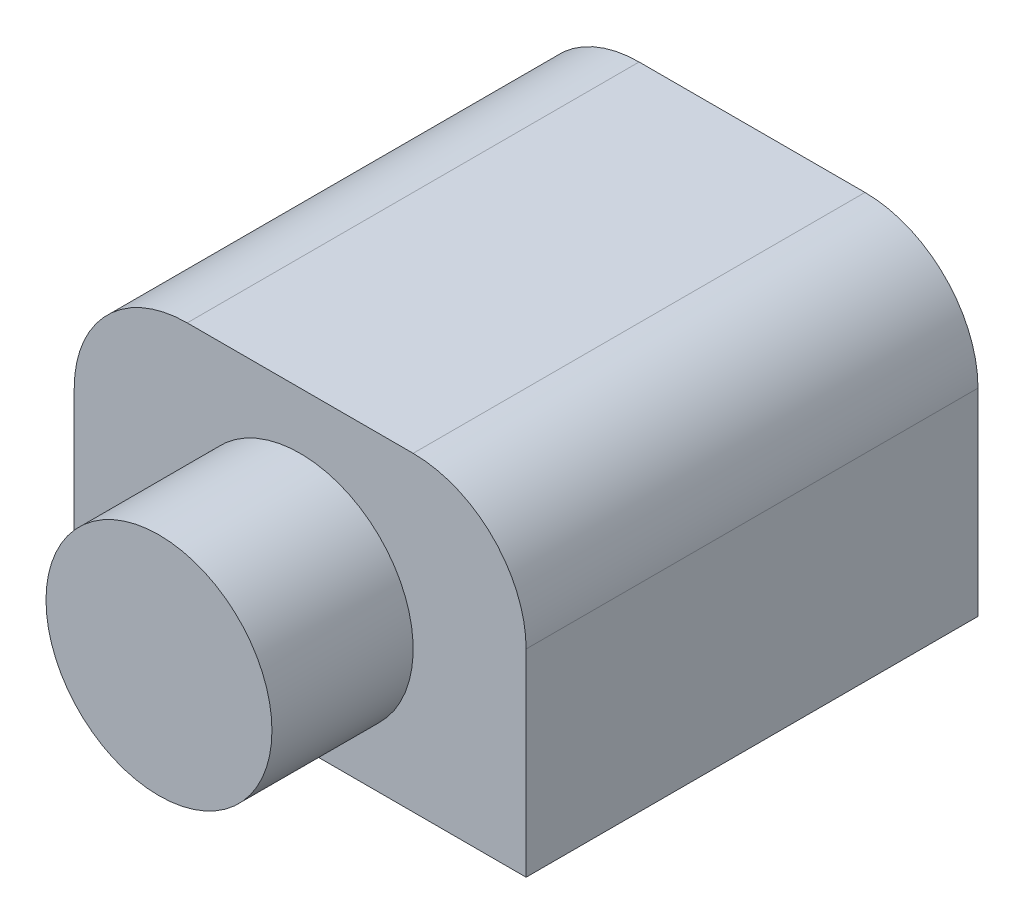
SolidWorks part; units mm, degrees
ref_plane "Plano frontal" through (0, 0, 0) normal (0, 0, 1) x (1, 0, 0)
ref_plane "Plano superior" through (0, 0, 0) normal (0, 1, 0) x (1, 0, 0)
ref_plane "Plano direito" through (0, 0, 0) normal (1, 0, 0) x (0, 0, -1)
sketch "Esboço1" plane through (0, 0, 0) normal (0, 1, 0) x (1, 0, 0)
  line L1 (40, -40) -> (-40, -40)
  line L2 (40, -40) -> (40, 40)
  line L3 (40, 40) -> (-40, 40)
  line L4 (-40, -40) -> (-40, 40)
  line L5 (40, -40) -> (-40, 40) construction
  line L6 (40, 40) -> (-40, -40) construction
  point P0 (0, 0)
  dimension "D1" = 80
extrude "Ressalto-extrusão1" add sketch "Esboço1" along normal blind 190
fillet "Filete2" radius 20 2 edges at (40, 190, 0) (-40, 190, 0)
sketch "Esboço2" plane through (0, 0, 40) normal (0, 0, 1) x (1, 0, 0)
  line L1 (-20, 190) -> (20, 190) construction
  line L2 (0, -52.3276) -> (0, 52.3276) construction
  circle A0 centre (0, 160) radius 20
  point P9 (0, 0)
  dimension "D1" = 40
  dimension "D2" = 30
extrude "Ressalto-extrusão2" add sketch "Esboço2" along normal blind 25
sketch "Esboço3" plane through (0, 0, 0) normal (0, -1, 0) x (-1, 0, 0)
  line L0 (40, -40) -> (-40, -40) construction
  line L1 (-35, 35) -> (35, 35)
  line L2 (-35, 35) -> (-35, -35)
  line L3 (-35, -35) -> (35, -35)
  line L4 (35, 35) -> (35, -35)
  line L5 (-35, 35) -> (35, -35) construction
  line L6 (-35, -35) -> (35, 35) construction
  point P0 (0, 0)
  dimension "D1" = 5
extrude "Corte-extrusão1" cut sketch "Esboço3" against normal blind 135
sketch "Esboço4" plane through (0, 0, 40) normal (0, 0, 1) x (1, 0, 0)
  line L0 (-20, 190) -> (20, 190) construction
  line L1 (-40, 170) -> (-40, 0) construction
  circle A0 centre (0, 90) radius 15
  dimension "D3" = 30
  dimension "D1" = 100
  dimension "D2" = 40
extrude "Corte-extrusão2" cut sketch "Esboço4" along direction (0, 0, -1) on the side against the normal up to surface (5 mm away)
ref_plane "Plano1" through (0, 135, 0) normal (0, 1, 0) x (1, 0, 0)
other "Corte de superfície1"
